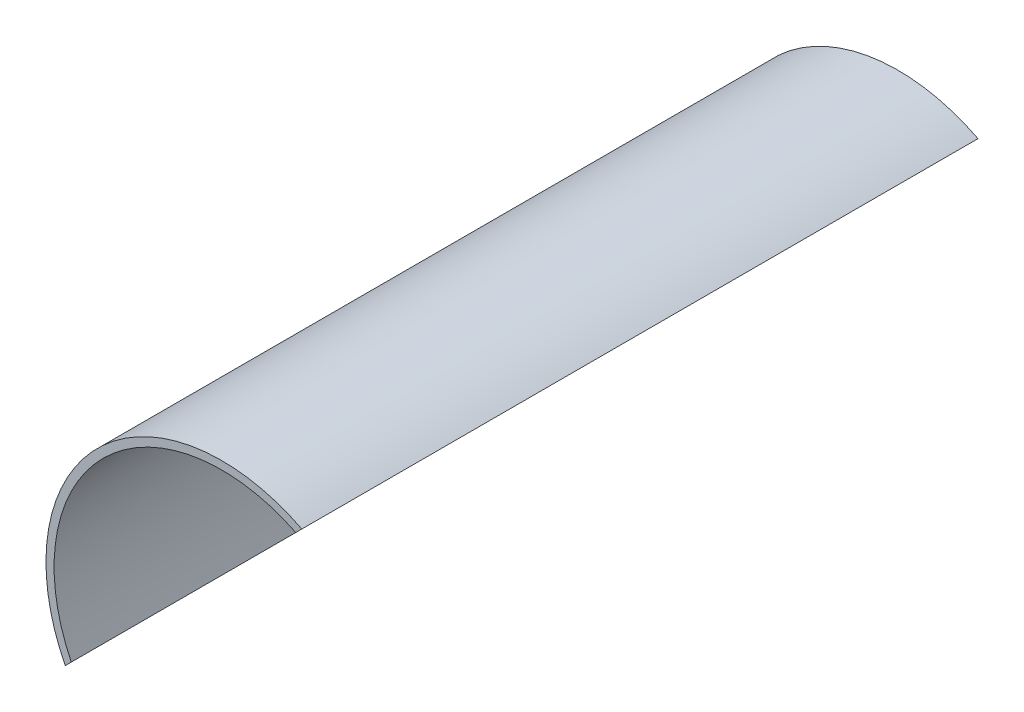
SolidWorks part; units mm, degrees
material "Polyetheretherketone (PEEK)"
ref_plane "Front Plane" through (0, 0, 0) normal (0, 0, 1) x (1, 0, 0)
ref_plane "Top Plane" through (0, 0, 0) normal (0, 1, 0) x (1, 0, 0)
ref_plane "Right Plane" through (0, 0, 0) normal (1, 0, 0) x (0, 0, -1)
sketch "Sketch1" plane through (0, 0, 0) normal (0, 0, 1) x (1, 0, 0)
  circle A0 centre (0, 0) radius 62
  circle A1 centre (0, 0) radius 65
  dimension "D1" = 124
  dimension "D2" = 3
extrude "Boss-Extrude1" add sketch "Sketch1" along normal blind 250
sketch "Sketch2" plane through (0, 0, 0) normal (0, 1, 0) x (1, 0, 0)
  line L0 (62, 0) -> (-62, 0) construction
  circle A0 centre (0, -224) radius 1
  circle A1 centre (0, -264) radius 1
  dimension "D1" = 2
  dimension "D3" = 2
  dimension "D2" = 224
  dimension "D4" = 40
ref_plane "Plane1" through (0, 0, 0) normal (-0.7071, 0.7071, 0) x (0.7071, 0.7071, 0)
ref_plane "Plane2" through (-14.1421, 14.1421, 0) normal (-0.7071, 0.7071, 0) x (0.7071, 0.7071, 0)
sketch "Sketch4" plane through (-14.1421, 14.1421, 0) normal (-0.7071, 0.7071, 0) x (0.7071, 0.7071, 0)
  line L0 (-65, 0) -> (-65, -250) construction
  line L1 (-65, 0) -> (65, 0)
  line L2 (-65, 0) -> (-65, -250)
  line L3 (-65, -250) -> (65, -250)
  line L4 (65, 0) -> (65, -250)
  line L5 (65, -250) -> (65, 0) construction
  line L6 (65, 0) -> (-65, 0) construction
  dimension "D1" = 0
  dimension "D2" = 250
extrude "Cut-Extrude4" cut sketch "Sketch4" against normal blind 516
sketch "Sketch5" plane through (0, 0, 0) normal (0, 0, -1) x (-1, 0, 0)
  line L1 (0, 0) -> (45.9619, 45.9619)
  line L2 (1, 0) -> (-1, 0) construction
  line L3 (45.9619, 45.9619) -> (84.5805, 7.3433) construction
  circle A0 centre (0, 0) radius 65 construction
